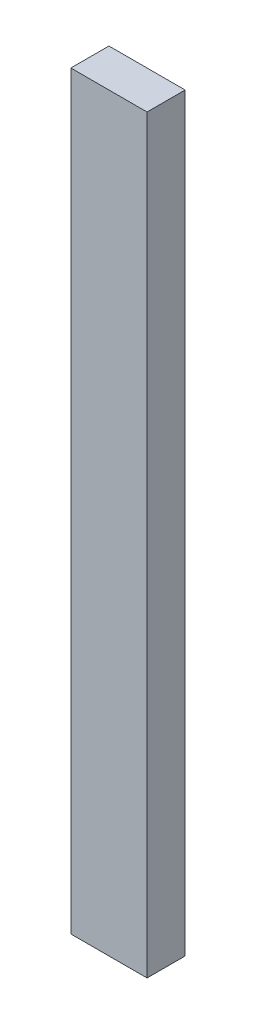
SolidWorks part; units mm, degrees
material "Balsa"
ref_plane "Front Plane" through (0, 0, 0) normal (0, 0, 1) x (1, 0, 0)
ref_plane "Top Plane" through (0, 0, 0) normal (0, 1, 0) x (1, 0, 0)
ref_plane "Right Plane" through (0, 0, 0) normal (1, 0, 0) x (0, 0, -1)
sketch "Sketch1" plane through (0, 0, 0) normal (0, 1, 0) x (1, 0, 0)
  line L1 (-25.4, -12.7) -> (25.4, -12.7)
  line L2 (-25.4, -12.7) -> (-25.4, 12.7)
  line L3 (-25.4, 12.7) -> (25.4, 12.7)
  line L4 (25.4, -12.7) -> (25.4, 12.7)
  line L5 (-25.4, -12.7) -> (25.4, 12.7) construction
  line L6 (-25.4, 12.7) -> (25.4, -12.7) construction
  point P0 (0, 0)
  dimension "D1" = 50.8
  dimension "D2" = 25.4
extrude "Boss-Extrude1" add sketch "Sketch1" along normal mid plane 500
